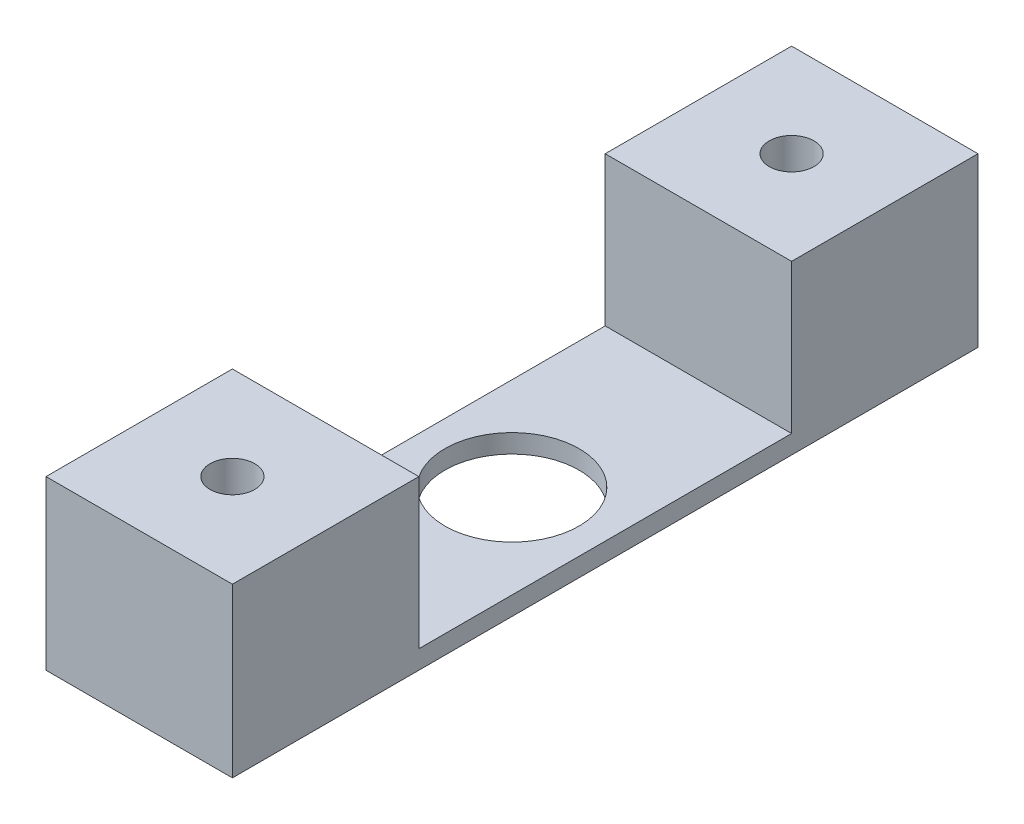
SolidWorks part; units mm, degrees
ref_plane "Piano frontale" through (0, 0, 0) normal (0, 0, 1) x (1, 0, 0)
ref_plane "Piano superiore" through (0, 0, 0) normal (0, 1, 0) x (1, 0, 0)
ref_plane "Piano destro" through (0, 0, 0) normal (1, 0, 0) x (0, 0, -1)
sketch "Schizzo1" plane through (0, 0, 0) normal (0, 1, 0) x (1, 0, 0)
  line L1 (-5, 20) -> (5, 20)
  line L2 (-5, 20) -> (-5, -20)
  line L3 (-5, -20) -> (5, -20)
  line L4 (5, 20) -> (5, -20)
  line L5 (-5, 20) -> (5, -20) construction
  line L6 (-5, -20) -> (5, 20) construction
  point P0 (0, 0)
  dimension "D1" = 40
  dimension "D2" = 10
extrude "Estrusione-Estrusione1" add sketch "Schizzo1" along normal blind 9
sketch "Schizzo2" plane through (0, 9, 0) normal (0, 1, 0) x (1, 0, 0)
  line L0 (5, -20) -> (5, 20) construction
  line L1 (-5, 10) -> (5, 10)
  line L2 (-5, 10) -> (-5, -10)
  line L3 (-5, -10) -> (5, -10)
  line L4 (5, 10) -> (5, -10)
  line L5 (-5, 10) -> (5, -10) construction
  line L6 (-5, -10) -> (5, 10) construction
  point P0 (0, 0)
  dimension "D1" = 20
extrude "Taglio-Estrusione1" cut sketch "Schizzo2" against normal blind 8
hole_wizard "Foro per Vite M2-1" positions "Schizzo3" profile "Schizzo4" hole size "M2" standard "ISO"
sketch "Schizzo3" plane through (0, 9, 0) normal (0, 1, 0) x (1, 0, 0)
  line L0 (-5, -10) -> (5, -10) construction
  line L1 (5, 10) -> (-5, 10) construction
  point P0 (0, -15)
  point P2 (0, 15)
  dimension "D1" = 5
  dimension "D2" = 5
sketch "Schizzo4" plane through (0, 9, 15) normal (1, 0, 0) x (0, 0, 1)
  line L0 (0, 0) -> (0, 6.721)
  line L1 (0, 6.721) -> (1.2, 6)
  line L2 (1.2, 6) -> (1.2, 0)
  line L5 (1.2, 0) -> (0, 0)
  line L10 (0, 6.721) -> (-1.2, 6) construction
  line L11 (0, -6.35) -> (0, 107.95) construction
  dimension "Hole Dia." = 2.4
  dimension "Hole Depth" = 6
  dimension "Drill Angle" = 118
hole_wizard "Foro per Vite M2-2" positions "Schizzo5" profile "Schizzo6" hole size "M2" standard "ISO" end condition through all
sketch "Schizzo5" plane through (0, 1, 0) normal (0, 1, 0) x (1, 0, 0)
  point P0 (0, 0)
sketch "Schizzo6" plane through (0, 1, 0) normal (1, 0, 0) x (0, 0, 1)
  line L0 (0, 0) -> (0, 1)
  line L1 (0, 1) -> (3.6, 1)
  line L2 (3.6, 1) -> (3.6, 0)
  line L5 (3.6, 0) -> (0, 0)
  line L11 (0, -6.35) -> (0, 107.95) construction
  dimension "Thru Hole Dia." = 7.2
  dimension "Thru Hole Depth" = 1
